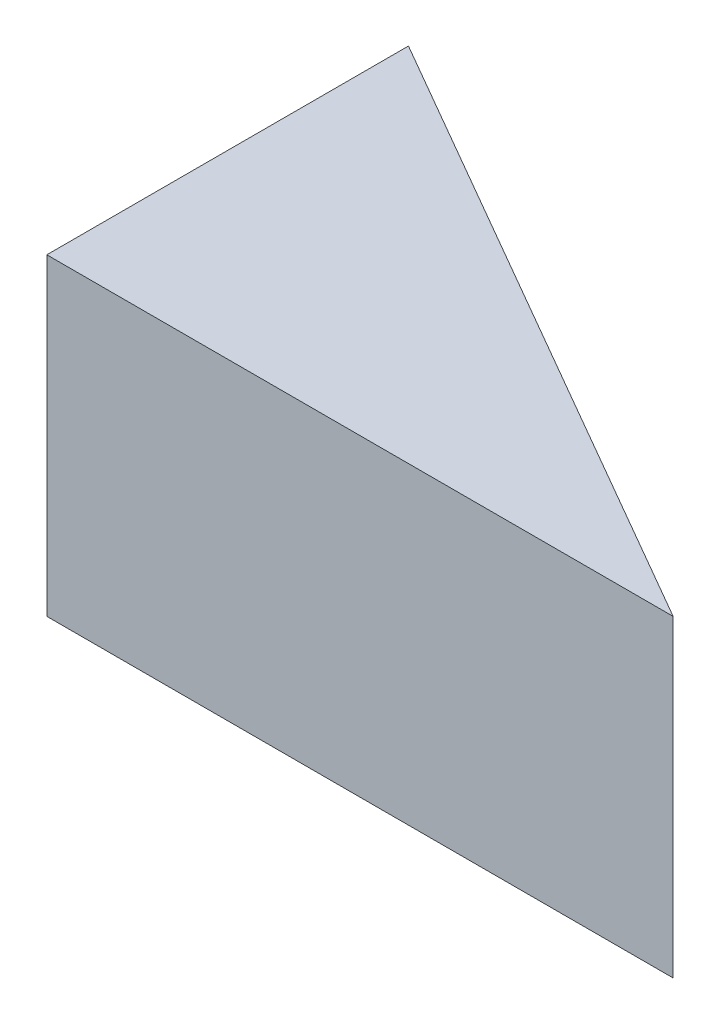
SolidWorks part; units mm, degrees
ref_plane "Přední rovina" through (0, 0, 0) normal (0, 0, 1) x (1, 0, 0)
ref_plane "Horní rovina" through (0, 0, 0) normal (0, 1, 0) x (1, 0, 0)
ref_plane "Pravá rovina" through (0, 0, 0) normal (1, 0, 0) x (0, 0, -1)
sketch "Sketch1" plane through (0, 0, 0) normal (0, 1, 0) x (1, 0, 0)
  line L0 (0, 0) -> (40, 0)
  line L1 (40, 0) -> (0, 23.094)
  line L2 (0, 23.094) -> (0, 0)
  point P4 (0, 0)
  point P5 (0, 0)
  point P6 (0, 16.8591)
  dimension "D1" = 30
  dimension "D2" = 40
extrude "Boss-Extrude1" add sketch "Sketch1" along normal blind 20
